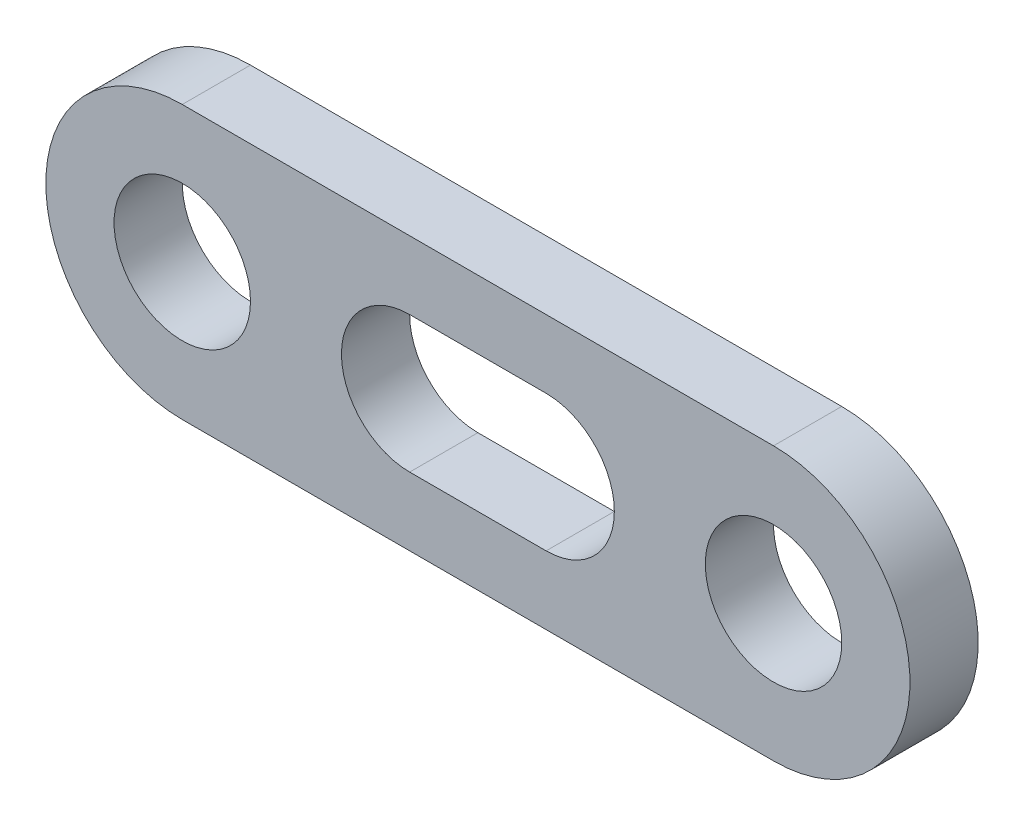
SolidWorks part; units mm, degrees
ref_plane "前视" through (0, 0, 0) normal (0, 0, 1) x (1, 0, 0)
ref_plane "上视" through (0, 0, 0) normal (0, 1, 0) x (1, 0, 0)
ref_plane "右视" through (0, 0, 0) normal (1, 0, 0) x (0, 0, -1)
sketch "草图2" plane through (0, 0, 0) normal (0, 0, 1) x (1, 0, 0)
  line L0 (0, 6) -> (26, 6)
  line L1 (0, -6) -> (26, -6)
  line L2 (10, 3) -> (16, 3)
  line L3 (10, -3) -> (16, -3)
  line L4 (-8.0174, 0) -> (37.0477, 0) construction
  arc A0 (0, 6) -> (0, -6) centre (0, 0) ccw
  arc A1 (26, -6) -> (26, 6) centre (26, 0) ccw
  circle A2 centre (0, 0) radius 3
  circle A3 centre (26, 0) radius 3
  arc A4 (10, 3) -> (10, -3) centre (10, 0) ccw
  arc A5 (16, -3) -> (16, 3) centre (16, 0) ccw
  dimension "D1" = 12
  dimension "D2" = 12
  dimension "D3" = 6
  dimension "D4" = 6
  dimension "D8" = 6
  dimension "D9" = 6
  dimension "D5" = 26
  dimension "D6" = 10
  dimension "D7" = 10
extrude "凸台-拉伸1" add sketch "草图2" along normal blind 3
